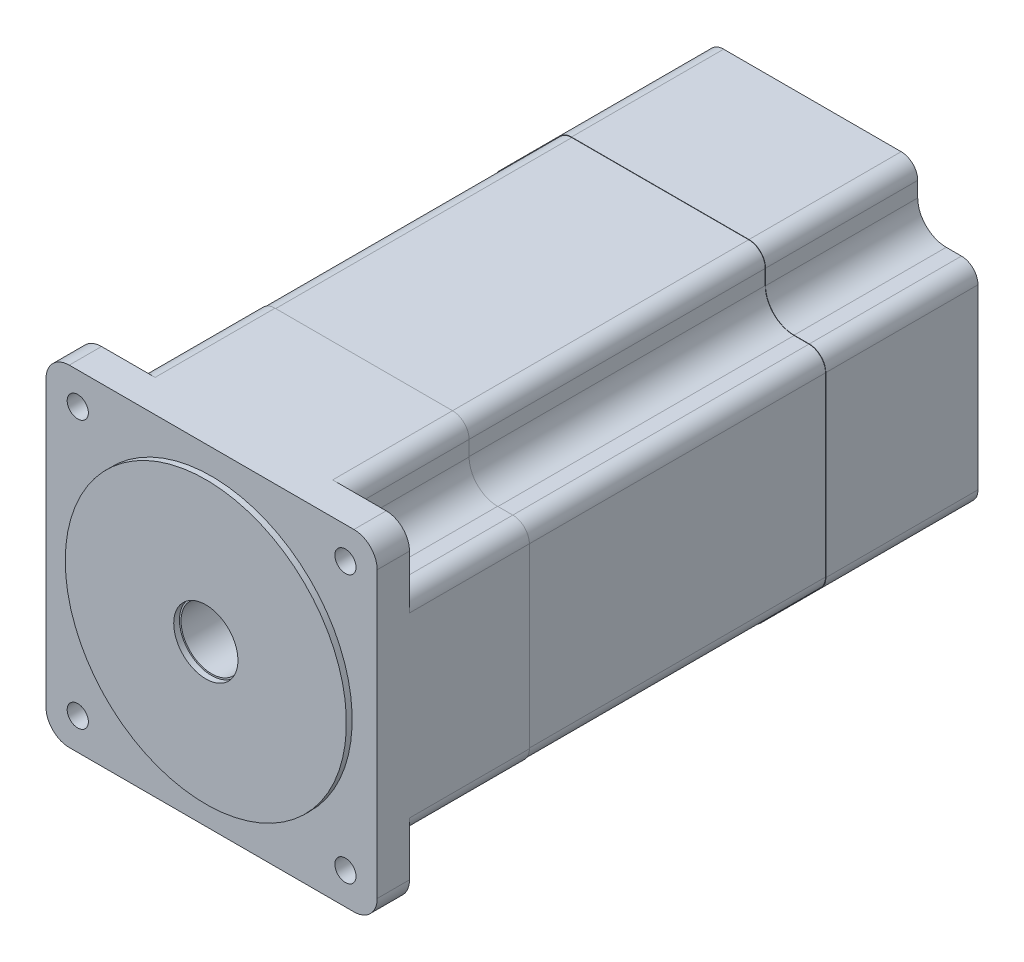
SolidWorks part; units mm, degrees
ref_plane "Front" through (0, 0, 0) normal (0, 0, 1) x (1, 0, 0)
ref_plane "Top" through (0, 0, 0) normal (0, 1, 0) x (1, 0, 0)
ref_plane "Right" through (0, 0, 0) normal (1, 0, 0) x (0, 0, -1)
sketch "Support-Front" plane through (0, 0, 0) normal (0, 0, 1) x (1, 0, 0)
  line L0 (-43, 0) -> (43, 0) construction
  line L1 (-36.9567, 43) -> (36.9567, 43)
  line L2 (-43, 36.9567) -> (-43, -36.9567)
  line L3 (-36.9567, -43) -> (36.9567, -43)
  line L4 (43, 36.9567) -> (43, -36.9567)
  line L5 (0, 43) -> (43, 36.9567) construction
  line L6 (0, 43) -> (0, -43) construction
  line L7 (-36.9567, -42.914) -> (36.9567, -42.914)
  line L8 (42.914, 36.9567) -> (42.914, -36.9567)
  line L9 (-36.9567, 42.914) -> (36.9567, 42.914)
  line L10 (-42.914, 36.9567) -> (-42.914, -36.9567)
  arc A0 (-43, 36.9567) -> (-36.9567, 43) centre (-36.9567, 36.9567) cw
  arc A1 (-43, -36.9567) -> (-36.9567, -43) centre (-36.9567, -36.9567) ccw
  arc A2 (43, -36.9567) -> (36.9567, -43) centre (36.9567, -36.9567) cw
  arc A3 (36.9567, 43) -> (43, 36.9567) centre (36.9567, 36.9567) cw
  circle A4 centre (0, 0) radius 58.308 construction
  arc A5 (42.914, -36.9567) -> (36.9567, -42.914) centre (36.9567, -36.9567) cw
  arc A6 (36.9567, 42.914) -> (42.914, 36.9567) centre (36.9567, 36.9567) cw
  arc A7 (-42.914, 36.9567) -> (-36.9567, 42.914) centre (-36.9567, 36.9567) cw
  arc A8 (-42.914, -36.9567) -> (-36.9567, -42.914) centre (-36.9567, -36.9567) ccw
  point P6 (0, 0)
  dimension "Height" = 86
  dimension "Width" = 86
  dimension "D1" = 8
  dimension "Cosmetic-Center-Cut" = 0.086
sketch "Support-Front-Hole" plane through (0, 0, 0) normal (0, 0, 1) x (1, 0, 0)
  line L0 (-43, 0) -> (43, 0) construction
  line L1 (0, 43) -> (0, -43) construction
  line L2 (-43, 0) -> (43, 0) construction
  line L3 (0, 43) -> (0, -43) construction
  circle A0 centre (-34.75, 34.75) radius 2.75
  circle A1 centre (34.75, 34.75) radius 2.75
  circle A2 centre (-34.75, -34.75) radius 2.75
  circle A3 centre (34.75, -34.75) radius 2.75
  circle A4 centre (23, 0) radius 1.25
  circle A5 centre (-23, 0) radius 1.25
  circle A6 centre (0, 0) radius 23 construction
  dimension "Diam-Fixing-Hole" = 5.5
  dimension "Dist-Back-Fixing-Hole" = 46
  dimension "Diam-Back-Fixing-Hole" = 2.5
  dimension "Width-Fixing-Hole" = 69.5
  dimension "Height-Fixing-Hole" = 69.5
sketch "Support-Right" plane through (0, 0, 0) normal (1, 0, 0) x (0, 0, -1)
  line L0 (0, 0) -> (156, 0) construction
  line L1 (156, 58.308) -> (156, -58.308)
  line L2 (156, 58.308) -> (0, 58.308)
  line L3 (156, 7.9375) -> (0, 7.9375)
  line L4 (156, -58.308) -> (0, -58.308)
  line L5 (0, 43) -> (0, -43) construction
  line L6 (156, -7.9375) -> (0, -7.9375)
  line L7 (78, 58.308) -> (78, 0) construction
  line L8 (78, 29.154) -> (116.491, 29.154) construction
  line L9 (116.491, 29.154) -> (117.509, 29.154)
  line L10 (117.509, 29.154) -> (156, 29.154) construction
  line L11 (116.491, 29.154) -> (116.491, 58.308)
  line L12 (116.491, 58.308) -> (117.509, 29.154) construction
  line L13 (117.509, 29.154) -> (117.509, -29.154)
  line L14 (116.491, -29.154) -> (116.491, -58.308)
  line L15 (116.491, -29.154) -> (117.509, -29.154)
  line L16 (39.509, 58.308) -> (38.491, 29.154) construction
  line L17 (39.509, -29.154) -> (38.491, -29.154)
  line L18 (39.509, -29.154) -> (39.509, -58.308)
  line L19 (38.491, 29.154) -> (38.491, -29.154)
  line L20 (39.509, 29.154) -> (39.509, 58.308)
  line L21 (39.509, 29.154) -> (38.491, 29.154)
  line L22 (0, 58.308) -> (0, 36.5)
  line L25 (0, 36.5) -> (-1.5, 36.5)
  line L26 (-1.5, 36.5) -> (-1.5, 7.9375)
  line L27 (-1.5, 7.9375) -> (0, 7.9375)
  line L28 (0, 7.9375) -> (-1.5, 8.3394) construction
  line L29 (-1.5, 8.3394) -> (0, 8.3394)
  line L30 (0, 8.3394) -> (0, 7.9375)
  line L31 (136.7545, 29.154) -> (136.7545, -34.407) construction
  line L32 (0, -8.3394) -> (0, -7.9375)
  line L33 (-1.5, -8.3394) -> (0, -8.3394)
  line L34 (-1.5, -7.9375) -> (0, -7.9375)
  line L35 (-1.5, -36.5) -> (-1.5, -7.9375)
  line L36 (0, -36.5) -> (-1.5, -36.5)
  line L37 (134.7545, -7.9375) -> (134.7545, -53)
  line L38 (134.7545, -53) -> (138.7545, -53)
  line L39 (0, -58.308) -> (0, -36.5)
  line L41 (138.7545, -53) -> (138.7545, -7.9375)
  line L43 (0, 49.928) -> (8.38, 49.928) construction
  line L44 (8.38, 49.928) -> (8.38, 58.308) construction
  line L45 (0, -43) -> (156, -43) construction
  line L46 (136.7545, -53) -> (136.7545, -7.9375) construction
  line L47 (117.509, 2.5) -> (156, 2.5)
  line L48 (117.509, -2.5) -> (156, -2.5)
  line L49 (154.5, 2.5) -> (154.5, 2.9019)
  line L50 (154.5, 2.9019) -> (156, 2.9019)
  line L51 (154.5, -2.5) -> (154.5, -2.9019)
  line L52 (154.5, -2.9019) -> (156, -2.9019)
  point P5 (156, 0)
  point P10 (78, 29.154)
  point P26 (117.509, 0)
  point P32 (38.491, 0)
  point P49 (136.7545, -53)
  dimension "D1" = 2
  dimension "Length" = 156
  dimension "Diam-Hole-Shaft" = 15.875
  dimension "Diam-Front" = 73
  dimension "D4" = 15
  dimension "Length-Front" = 1.5
  dimension "Cut-Corner" = 8.38
  dimension "Diam-Cable" = 4
  dimension "Length-Cable" = 10
  dimension "Diam-Hole-Shaft-Back" = 5
sketch "Support-Front-Cut" plane through (0, 0, 0) normal (0, 0, 1) x (1, 0, 0)
  line L0 (27.3493, 43) -> (27.3493, 34.75)
  line L1 (-36.9567, 43) -> (36.9567, 43) construction
  line L2 (34.75, 27.3493) -> (43, 27.3493)
  line L3 (43, 36.9567) -> (43, -36.9567) construction
  line L4 (0, 43) -> (0, -43) construction
  line L5 (-43, 0) -> (43, 0) construction
  line L6 (0, 43) -> (0, -43) construction
  line L7 (-43, 0) -> (43, 0) construction
  line L8 (0, 43) -> (43, 27.3493) construction
  line L9 (-34.75, 27.3493) -> (-43, 27.3493)
  line L10 (-27.3493, 43) -> (-27.3493, 34.75)
  line L11 (-27.3493, -43) -> (-27.3493, -34.75)
  line L12 (-34.75, -27.3493) -> (-43, -27.3493)
  line L13 (34.75, -27.3493) -> (43, -27.3493)
  line L14 (27.3493, -43) -> (27.3493, -34.75)
  line L15 (27.2633, 43) -> (27.2633, 34.75)
  line L16 (34.75, 27.2633) -> (43, 27.2633)
  line L17 (-34.75, 27.2633) -> (-43, 27.2633)
  line L18 (-27.2633, 43) -> (-27.2633, 34.75)
  line L19 (-27.2633, -43) -> (-27.2633, -34.75)
  line L20 (-34.75, -27.2633) -> (-43, -27.2633)
  line L21 (27.2633, -43) -> (27.2633, -34.75)
  line L22 (34.75, -27.2633) -> (43, -27.2633)
  arc A0 (27.3493, 34.75) -> (34.75, 27.3493) centre (34.75, 34.75) ccw
  arc A1 (-27.3493, 34.75) -> (-34.75, 27.3493) centre (-34.75, 34.75) cw
  arc A2 (-27.3493, -34.75) -> (-34.75, -27.3493) centre (-34.75, -34.75) ccw
  arc A3 (27.3493, -34.75) -> (34.75, -27.3493) centre (34.75, -34.75) cw
  arc A4 (27.2633, 34.75) -> (34.75, 27.2633) centre (34.75, 34.75) ccw
  arc A5 (-27.2633, 34.75) -> (-34.75, 27.2633) centre (-34.75, 34.75) cw
  arc A6 (-27.2633, -34.75) -> (-34.75, -27.2633) centre (-34.75, -34.75) ccw
  arc A7 (27.2633, -34.75) -> (34.75, -27.2633) centre (34.75, -34.75) cw
  dimension "Cosmetic-Center-Cut" = 0.086
  dimension "D1" = 340
ref_axis "Ref-Axis-Center" through (0, 0, -80.9) along (0, 0, 1)
ref_plane "Ref-Plane-Front-Center" through (0, 0, -39.509) normal (0, 0, 1) x (1, 0, 0)
ref_plane "Ref-Plane-Back-Center" through (0, 0, -116.491) normal (0, 0, 1) x (1, 0, 0)
ref_plane "Ref-Plane-Corner" through (0, 0, -8.38) normal (0, 0, 1) x (1, 0, 0)
sketch "Sketch5" plane through (0, 0, 0) normal (1, 0, 0) x (0, 0, -1)
  line L0 (0, 8.3394) -> (0, 7.9375) construction
  line L1 (-1.5, 8.3394) -> (0, 8.3394) construction
  line L2 (156, 7.9375) -> (0, 7.9375) construction
  line L3 (-1.5, 36.5) -> (-1.5, 7.9375) construction
  line L4 (0, 36.5) -> (-1.5, 36.5) construction
  line L7 (0, 58.308) -> (0, 36.5) construction
  line L8 (156, 58.308) -> (0, 58.308) construction
  line L9 (39.509, 29.154) -> (39.509, 58.308) construction
  line L10 (39.509, 29.154) -> (38.491, 29.154) construction
  line L11 (38.491, 29.154) -> (38.491, -29.154) construction
  line L14 (0, 8.3394) -> (0, 7.9375)
  line L15 (-1.5, 8.3394) -> (0, 8.3394)
  line L16 (38.491, 7.9375) -> (0, 7.9375)
  line L17 (-1.5, 36.5) -> (-1.5, 8.3394)
  line L18 (0, 36.5) -> (-1.5, 36.5)
  line L21 (0, 58.308) -> (0, 36.5)
  line L22 (39.509, 58.308) -> (0, 58.308)
  line L23 (39.509, 29.154) -> (39.509, 58.308)
  line L24 (39.509, 29.154) -> (38.491, 29.154)
  line L25 (38.491, 29.154) -> (38.491, 7.9375)
revolve "Body-Front" add sketch "Sketch5" angle 360 about axis through (0, 0, -80.9) along (0, 0, 1)
sketch "Sketch6" plane through (0, 0, 0) normal (1, 0, 0) x (0, 0, -1)
  line L0 (156, 7.9375) -> (0, 7.9375) construction
  line L1 (39.509, 29.154) -> (39.509, 58.308) construction
  line L3 (116.491, 29.154) -> (117.509, 29.154) construction
  line L4 (117.509, 29.154) -> (117.509, -29.154) construction
  line L5 (116.491, 29.154) -> (116.491, 58.308) construction
  line L6 (39.509, 29.154) -> (39.509, 58.308)
  line L7 (116.491, 29.154) -> (116.491, 58.308)
  line L9 (38.491, 29.154) -> (38.491, -29.154) construction
  line L10 (39.509, 29.154) -> (38.491, 29.154) construction
  line L12 (117.509, 7.9375) -> (38.491, 7.9375)
  line L13 (156, 58.308) -> (0, 58.308) construction
  line L15 (116.491, 29.154) -> (117.509, 29.154)
  line L16 (117.509, 29.154) -> (117.509, 7.9375)
  line L18 (116.491, 58.308) -> (39.509, 58.308)
  line L21 (38.491, 29.154) -> (38.491, 7.9375)
  line L22 (39.509, 29.154) -> (38.491, 29.154)
revolve "Body-Middle" add sketch "Sketch6" angle 360 about axis through (0, 0, -80.9) along (0, 0, 1)
sketch "Sketch7" plane through (0, 0, 0) normal (1, 0, 0) x (0, 0, -1)
  line L2 (156, 58.308) -> (0, 58.308) construction
  line L3 (116.491, 29.154) -> (116.491, 58.308) construction
  line L4 (116.491, 29.154) -> (117.509, 29.154) construction
  line L8 (117.509, 2.5) -> (156, 2.5) construction
  line L9 (154.5, 2.5) -> (154.5, 2.9019) construction
  line L10 (156, 58.308) -> (116.491, 58.308)
  line L11 (116.491, 29.154) -> (116.491, 58.308)
  line L12 (116.491, 29.154) -> (117.509, 29.154)
  line L13 (154.5, 2.9019) -> (156, 2.9019) construction
  line L14 (156, 58.308) -> (156, -58.308) construction
  line L15 (117.509, 29.154) -> (117.509, -29.154) construction
  line L16 (117.509, 2.5) -> (154.5, 2.5)
  line L17 (154.5, 2.5) -> (154.5, 2.9019)
  line L18 (154.5, 2.9019) -> (156, 2.9019)
  line L19 (156, 58.308) -> (156, 2.9019)
  line L20 (117.509, 29.154) -> (117.509, 2.5)
revolve "Body-Back" add sketch "Sketch7" angle 360 about axis through (0, 0, -80.9) along (0, 0, 1)
sketch "Sketch9" plane through (0, 0, 0) normal (0, 0, 1) x (1, 0, 0)
  line L0 (-36.9567, 43) -> (36.9567, 43) construction
  line L1 (-43, 36.9567) -> (-43, -36.9567) construction
  line L2 (-36.9567, -43) -> (36.9567, -43) construction
  line L3 (43, 36.9567) -> (43, -36.9567) construction
  line L4 (-36.9567, 43) -> (36.9567, 43)
  line L5 (-43, 36.9567) -> (-43, -36.9567)
  line L6 (-36.9567, -43) -> (36.9567, -43)
  line L7 (43, 36.9567) -> (43, -36.9567)
  arc A0 (43, 36.9567) -> (36.9567, 43) centre (36.9567, 36.9567) ccw construction
  arc A1 (-36.9567, 43) -> (-43, 36.9567) centre (-36.9567, 36.9567) ccw construction
  arc A2 (-43, -36.9567) -> (-36.9567, -43) centre (-36.9567, -36.9567) ccw construction
  arc A3 (36.9567, -43) -> (43, -36.9567) centre (36.9567, -36.9567) ccw construction
  arc A4 (43, 36.9567) -> (36.9567, 43) centre (36.9567, 36.9567) ccw
  arc A5 (-36.9567, 43) -> (-43, 36.9567) centre (-36.9567, 36.9567) ccw
  arc A6 (-43, -36.9567) -> (-36.9567, -43) centre (-36.9567, -36.9567) ccw
  arc A7 (36.9567, -43) -> (43, -36.9567) centre (36.9567, -36.9567) ccw
extrude "Body-Cut" cut sketch "Sketch9" against normal through all flip side to cut
sketch "Sketch10" plane through (0, 0, -39.509) normal (0, 0, 1) x (1, 0, 0)
  line L4 (-42.914, 36.9567) -> (-42.914, -36.9567) construction
  line L5 (-36.9567, -42.914) -> (36.9567, -42.914) construction
  line L6 (42.914, 36.9567) -> (42.914, -36.9567) construction
  line L7 (-36.9567, 42.914) -> (36.9567, 42.914) construction
  line L8 (-42.914, 36.9567) -> (-42.914, -36.9567)
  line L9 (-36.9567, -42.914) -> (36.9567, -42.914)
  line L10 (42.914, 36.9567) -> (42.914, -36.9567)
  line L11 (-36.9567, 42.914) -> (36.9567, 42.914)
  arc A4 (-36.9567, 42.914) -> (-42.914, 36.9567) centre (-36.9567, 36.9567) ccw construction
  arc A5 (-42.914, -36.9567) -> (-36.9567, -42.914) centre (-36.9567, -36.9567) ccw construction
  arc A6 (36.9567, -42.914) -> (42.914, -36.9567) centre (36.9567, -36.9567) ccw construction
  arc A7 (42.914, 36.9567) -> (36.9567, 42.914) centre (36.9567, 36.9567) ccw construction
  arc A8 (-36.9567, 42.914) -> (-42.914, 36.9567) centre (-36.9567, 36.9567) ccw
  arc A9 (-42.914, -36.9567) -> (-36.9567, -42.914) centre (-36.9567, -36.9567) ccw
  arc A10 (36.9567, -42.914) -> (42.914, -36.9567) centre (36.9567, -36.9567) ccw
  arc A11 (42.914, 36.9567) -> (36.9567, 42.914) centre (36.9567, 36.9567) ccw
extrude "Body-Cut-Inner" cut sketch "Sketch10" against normal up to surface (76.9819 mm away) flip side to cut up to plane "Ref-Plane-Back-Center"
sketch "Sketch15" plane through (0, 0, 0) normal (0, 0, 1) x (1, 0, 0)
  circle A1 centre (34.75, -34.75) radius 2.75
  circle A2 centre (34.75, -34.75) radius 2.75
  circle A3 centre (-34.75, -34.75) radius 2.75
  circle A4 centre (-34.75, -34.75) radius 2.75
  circle A5 centre (34.75, 34.75) radius 2.75
  circle A6 centre (34.75, 34.75) radius 2.75
  circle A7 centre (-34.75, 34.75) radius 2.75
  circle A8 centre (-34.75, 34.75) radius 2.75
  dimension "D1" = 0
  dimension "D2" = 0
  dimension "D3" = 0
  dimension "D4" = 0
extrude "Cut-Fixing-Hole" cut sketch "Sketch15" against normal up to surface (39.509 mm away)
sketch "Sketch16" plane through (0, 0, -116.491) normal (0, 0, 1) x (1, 0, 0)
  circle A0 centre (-23, 0) radius 1.25 construction
  circle A1 centre (23, 0) radius 1.25 construction
  circle A2 centre (-23, 0) radius 1.25
  circle A3 centre (23, 0) radius 1.25
extrude "Cut-Back-Fixing-Hole" cut sketch "Sketch16" against normal through all
sketch "Sketch11" plane through (0, 0, -8.38) normal (0, 0, 1) x (1, 0, 0)
  line L4 (-27.3493, 43) -> (-27.3493, 34.75) construction
  line L5 (-34.75, 27.3493) -> (-43, 27.3493) construction
  line L6 (-34.75, -27.3493) -> (-43, -27.3493) construction
  line L7 (-27.3493, -43) -> (-27.3493, -34.75) construction
  line L11 (27.3493, -43) -> (27.3493, -34.75) construction
  line L12 (34.75, -27.3493) -> (43, -27.3493) construction
  line L13 (-43, 36.9567) -> (-43, -36.9567) construction
  line L14 (-36.9567, -43) -> (36.9567, -43) construction
  line L15 (43, 36.9567) -> (43, -36.9567) construction
  line L19 (-36.9567, 43) -> (36.9567, 43) construction
  line L20 (27.3493, 43) -> (27.3493, 34.75) construction
  line L21 (34.75, 27.3493) -> (43, 27.3493) construction
  line L22 (-27.3493, 43) -> (-27.3493, 34.75)
  line L23 (-34.75, 27.3493) -> (-43, 27.3493)
  line L24 (-34.75, -27.3493) -> (-43, -27.3493)
  line L25 (-27.3493, -43) -> (-27.3493, -34.75)
  line L26 (27.3493, -43) -> (27.3493, -34.75)
  line L27 (34.75, -27.3493) -> (43, -27.3493)
  line L28 (-43, 36.9567) -> (-43, 27.3493)
  line L29 (-36.9567, -43) -> (-27.3493, -43)
  line L30 (43, 36.9567) -> (43, 27.3493)
  line L31 (-36.9567, 43) -> (-27.3493, 43)
  line L32 (27.3493, 43) -> (27.3493, 34.75)
  line L33 (34.75, 27.3493) -> (43, 27.3493)
  line L34 (27.3493, 43) -> (36.9567, 43)
  line L35 (43, -27.3493) -> (43, -36.9567)
  line L36 (27.3493, -43) -> (36.9567, -43)
  line L37 (-43, -27.3493) -> (-43, -36.9567)
  arc A2 (-34.75, 27.3493) -> (-27.3493, 34.75) centre (-34.75, 34.75) ccw construction
  arc A3 (-27.3493, -34.75) -> (-34.75, -27.3493) centre (-34.75, -34.75) ccw construction
  arc A6 (34.75, -27.3493) -> (27.3493, -34.75) centre (34.75, -34.75) ccw construction
  arc A7 (36.9567, -43) -> (43, -36.9567) centre (36.9567, -36.9567) ccw construction
  arc A10 (-43, -36.9567) -> (-36.9567, -43) centre (-36.9567, -36.9567) ccw construction
  arc A11 (-36.9567, 43) -> (-43, 36.9567) centre (-36.9567, 36.9567) ccw construction
  arc A12 (43, 36.9567) -> (36.9567, 43) centre (36.9567, 36.9567) ccw construction
  arc A13 (27.3493, 34.75) -> (34.75, 27.3493) centre (34.75, 34.75) ccw construction
  arc A14 (-34.75, 27.3493) -> (-27.3493, 34.75) centre (-34.75, 34.75) ccw
  arc A15 (-27.3493, -34.75) -> (-34.75, -27.3493) centre (-34.75, -34.75) ccw
  arc A16 (34.75, -27.3493) -> (27.3493, -34.75) centre (34.75, -34.75) ccw
  arc A17 (36.9567, -43) -> (43, -36.9567) centre (36.9567, -36.9567) ccw
  arc A18 (-43, -36.9567) -> (-36.9567, -43) centre (-36.9567, -36.9567) ccw
  arc A19 (-36.9567, 43) -> (-43, 36.9567) centre (-36.9567, 36.9567) ccw
  arc A20 (43, 36.9567) -> (36.9567, 43) centre (36.9567, 36.9567) ccw
  arc A21 (27.3493, 34.75) -> (34.75, 27.3493) centre (34.75, 34.75) ccw
extrude "Cut-Corner" cut sketch "Sketch11" against normal through all
sketch "Sketch13" plane through (0, 0, -39.509) normal (0, 0, 1) x (1, 0, 0)
  line L0 (-34.75, 27.2633) -> (-43, 27.2633) construction
  line L1 (-27.2633, 43) -> (-27.2633, 34.75) construction
  line L2 (-34.75, -27.2633) -> (-43, -27.2633) construction
  line L3 (-27.2633, -43) -> (-27.2633, -34.75) construction
  line L4 (-43, 36.9567) -> (-43, -36.9567) construction
  line L5 (27.2633, -43) -> (27.2633, -34.75) construction
  line L6 (34.75, -27.2633) -> (43, -27.2633) construction
  line L7 (-36.9567, -43) -> (36.9567, -43) construction
  line L8 (43, 36.9567) -> (43, -36.9567) construction
  line L9 (-36.9567, 43) -> (36.9567, 43) construction
  line L10 (27.2633, 43) -> (27.2633, 34.75) construction
  line L11 (34.75, 27.2633) -> (43, 27.2633) construction
  line L12 (-34.75, 27.2633) -> (-43, 27.2633)
  line L13 (-27.2633, 43) -> (-27.2633, 34.75)
  line L14 (-34.75, -27.2633) -> (-43, -27.2633)
  line L15 (-27.2633, -43) -> (-27.2633, -34.75)
  line L16 (-43, 36.9567) -> (-43, 27.2633)
  line L17 (27.2633, -43) -> (27.2633, -34.75)
  line L18 (34.75, -27.2633) -> (43, -27.2633)
  line L19 (-36.9567, -43) -> (-27.2633, -43)
  line L20 (43, 36.9567) -> (43, 27.2633)
  line L21 (-36.9567, 43) -> (-27.2633, 43)
  line L22 (27.2633, 43) -> (27.2633, 34.75)
  line L23 (34.75, 27.2633) -> (43, 27.2633)
  line L24 (27.2633, 43) -> (36.9567, 43)
  line L25 (-43, -27.2633) -> (-43, -36.9567)
  line L26 (27.2633, -43) -> (36.9567, -43)
  line L27 (43, -27.2633) -> (43, -36.9567)
  arc A0 (-34.75, 27.2633) -> (-27.2633, 34.75) centre (-34.75, 34.75) ccw construction
  arc A1 (-36.9567, 43) -> (-43, 36.9567) centre (-36.9567, 36.9567) ccw construction
  arc A2 (-27.2633, -34.75) -> (-34.75, -27.2633) centre (-34.75, -34.75) ccw construction
  arc A3 (-43, -36.9567) -> (-36.9567, -43) centre (-36.9567, -36.9567) ccw construction
  arc A4 (34.75, -27.2633) -> (27.2633, -34.75) centre (34.75, -34.75) ccw construction
  arc A5 (36.9567, -43) -> (43, -36.9567) centre (36.9567, -36.9567) ccw construction
  arc A6 (43, 36.9567) -> (36.9567, 43) centre (36.9567, 36.9567) ccw construction
  arc A7 (27.2633, 34.75) -> (34.75, 27.2633) centre (34.75, 34.75) ccw construction
  arc A8 (-34.75, 27.2633) -> (-27.2633, 34.75) centre (-34.75, 34.75) ccw
  arc A9 (-36.9567, 43) -> (-43, 36.9567) centre (-36.9567, 36.9567) ccw
  arc A10 (-27.2633, -34.75) -> (-34.75, -27.2633) centre (-34.75, -34.75) ccw
  arc A11 (-43, -36.9567) -> (-36.9567, -43) centre (-36.9567, -36.9567) ccw
  arc A12 (34.75, -27.2633) -> (27.2633, -34.75) centre (34.75, -34.75) ccw
  arc A13 (36.9567, -43) -> (43, -36.9567) centre (36.9567, -36.9567) ccw
  arc A14 (43, 36.9567) -> (36.9567, 43) centre (36.9567, 36.9567) ccw
  arc A15 (27.2633, 34.75) -> (34.75, 27.2633) centre (34.75, 34.75) ccw
extrude "Cut-Corner-Inner" cut sketch "Sketch13" against normal up to surface (76.9819 mm away)
sketch "Sketch18" plane through (0, 0, 0) normal (1, 0, 0) x (0, 0, -1)
  line L0 (134.7545, -53) -> (138.7545, -53) construction
  line L1 (154.5, -2.9019) -> (134.7545, -2.9019) construction
  line L3 (134.7545, -7.9375) -> (134.7545, -53) construction
  line L4 (134.7545, -53) -> (136.7545, -53)
  line L5 (134.7545, -2.9019) -> (136.7545, -2.9019)
  line L7 (134.7545, -2.9019) -> (134.7545, -53)
  line L8 (136.7545, -53) -> (136.7545, -7.9375) construction
  line L9 (136.7545, -53) -> (136.7545, -2.9019)
revolve "Body-Cable" add sketch "Sketch18" angle 360 about L31
fillet "Cosmetic-Fillet-Inner" radius 4.3 8 edges at (-27.2633, -42.914, -78) (-42.914, -27.2633, -78) (-42.914, 27.2633, -78) (-27.2633, 42.914, -78) (27.2633, -42.914, -78) (42.914, -27.2633, -78) (42.914, 27.2633, -78) (27.2633, 42.914, -78)
fillet "Cosmetic-Fillet" radius 4.3 16 edges at (-27.3493, 43, -23.9445) (27.3493, 43, -23.9445) (43, 27.3493, -23.9445) (43, -27.3493, -23.9445) (27.3493, -43, -23.9445) (-43, 27.3493, -23.9445) (-43, -27.3493, -23.9445) (-27.3493, -43, -23.9445) (-27.3493, -43, -136.2455) (-43, -27.3493, -136.2455) (-43, 27.3493, -136.2455) (-27.3493, 43, -136.2455) (27.3493, -43, -136.2455) (43, -27.3493, -136.2455) (43, 27.3493, -136.2455) (27.3493, 43, -136.2455)
equation "\"Cosmetic-Center-Cut@Support-Front\"=\"Width@Support-Front\"*0.001"
equation "\"Cosmetic-Center-Cut@Support-Front-Cut\"=\"Cosmetic-Center-Cut@Support-Front\""
equation "\"D1@Cosmetic-Fillet-Inner\"=\"Height@Support-Front\"/20"
equation "\"D1@Cosmetic-Fillet\"=\"Height@Support-Front\"/20"
